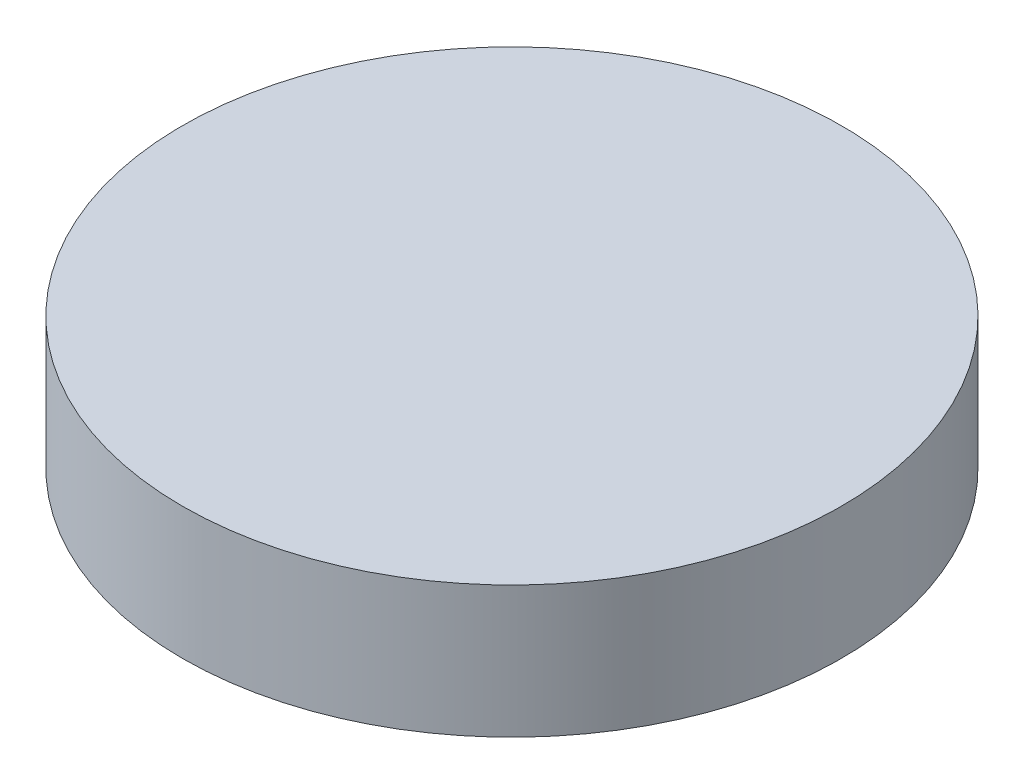
SolidWorks part; units mm, degrees
material "Полиуретановый гибкий пенопласт"
ref_plane "Спереди" through (0, 0, 0) normal (0, 0, 1) x (1, 0, 0)
ref_plane "Сверху" through (0, 0, 0) normal (0, 1, 0) x (1, 0, 0)
ref_plane "Справа" through (0, 0, 0) normal (1, 0, 0) x (0, 0, -1)
sketch "Эскиз1" plane through (0, 0, 0) normal (0, 1, 0) x (1, 0, 0)
  circle A0 centre (0, 0) radius 10
  dimension "D1" = 20
extrude "Бобышка-Вытянуть1" add sketch "Эскиз1" along normal blind 4
